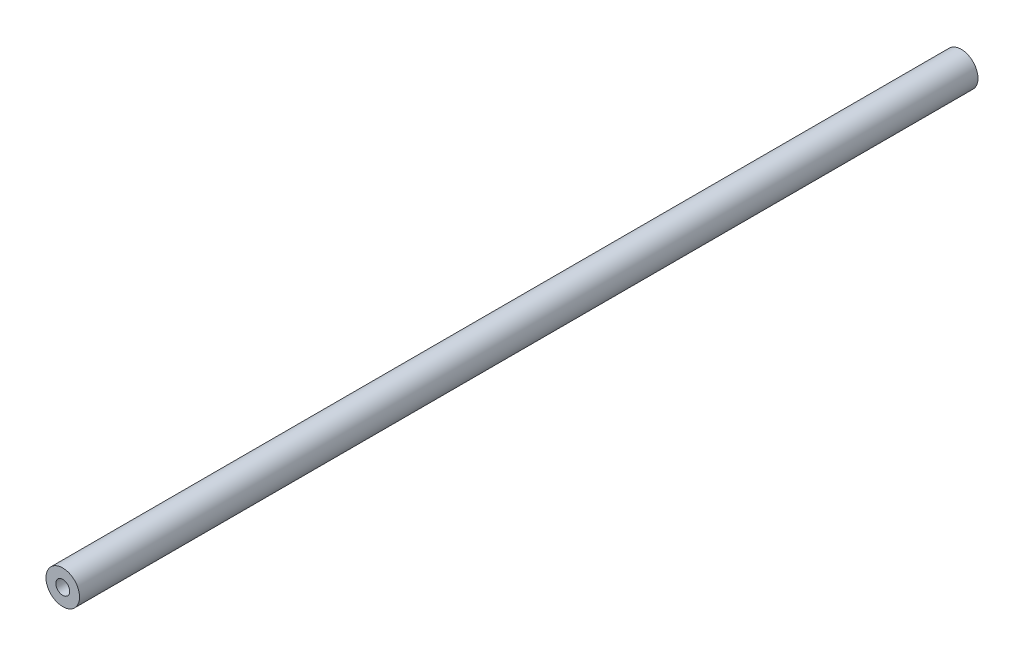
SolidWorks part; units mm, degrees
material "Латунь"
ref_plane "Спереди" through (0, 0, 0) normal (0, 0, 1) x (1, 0, 0)
ref_plane "Сверху" through (0, 0, 0) normal (0, 1, 0) x (1, 0, 0)
ref_plane "Справа" through (0, 0, 0) normal (1, 0, 0) x (0, 0, -1)
other "Configuration Table"
sketch "Эскиз1" plane through (0, 0, 0) normal (0, 0, 1) x (1, 0, 0)
  line L0 (235.7213, -388.4131) -> (236.321, -388.4131) construction
  circle A0 centre (0, 0) radius 4
  dimension "D1" = 8
extrude "Бобышка-Вытянуть1" add sketch "Эскиз1" along normal mid plane 214
sketch "Эскиз2" plane through (0, 0, 107) normal (0, 0, 1) x (1, 0, 0)
  circle A0 centre (0, 0) radius 1.25
  dimension "D1" = 2.5
sketch "Эскиз3" plane through (0, 0, -107) normal (0, 0, -1) x (-1, 0, 0)
  circle A0 centre (0, 0) radius 1.25
  dimension "D1" = 2.5
hole_wizard "Отверстие обработанное метчиком M4x0.71" positions "Эскиз4" profile "Эскиз5" tap size "M4x0.7" standard "Ansi Metric"
sketch "Эскиз4" plane through (0, 0, -107) normal (0, 0, -1) x (-1, 0, 0)
  point P0 (0, 0)
sketch "Эскиз5" plane through (0, 0, -107) normal (1, 0, 0) x (0, 1, 0)
  line L0 (0, 0) -> (0, 11.9914)
  line L1 (0, 11.9914) -> (1.65, 11)
  line L2 (1.65, 11) -> (1.65, 0)
  line L5 (1.65, 0) -> (0, 0)
  line L10 (0, 11.9914) -> (-1.65, 11) construction
  line L11 (0, -6.35) -> (0, 107.95) construction
  dimension "Диаметр сверла" = 3.3
  dimension "Глубина сверла" = 11
  dimension "Угол заточки сверла" = 118
hole_wizard "Отверстие обработанное метчиком M4x0.72" positions "Эскиз6" profile "Эскиз7" tap size "M4x0.7" standard "Ansi Metric"
sketch "Эскиз6" plane through (0, 0, 107) normal (0, 0, 1) x (1, 0, 0)
  point P0 (0, 0)
sketch "Эскиз7" plane through (0, 0, 107) normal (1, 0, 0) x (0, -1, 0)
  line L0 (0, 0) -> (0, 11.9914)
  line L1 (0, 11.9914) -> (1.65, 11)
  line L2 (1.65, 11) -> (1.65, 0)
  line L5 (1.65, 0) -> (0, 0)
  line L10 (0, 11.9914) -> (-1.65, 11) construction
  line L11 (0, -6.35) -> (0, 107.95) construction
  dimension "Диаметр сверла" = 3.3
  dimension "Глубина сверла" = 11
  dimension "Угол заточки сверла" = 118
sketch "Эскиз13" plane through (0, 0, 107) normal (0, 0, 1) x (1, 0, 0)
  line L0 (4, 0) -> (-4, 0) construction
  line L1 (0, 4) -> (0, -4) construction
  circle A0 centre (0, 0) radius 4 construction
  circle A1 centre (0, 0) radius 4
sketch "Эскиз14" plane through (0, 0, 107) normal (0, 0, 1) x (1, 0, 0)
